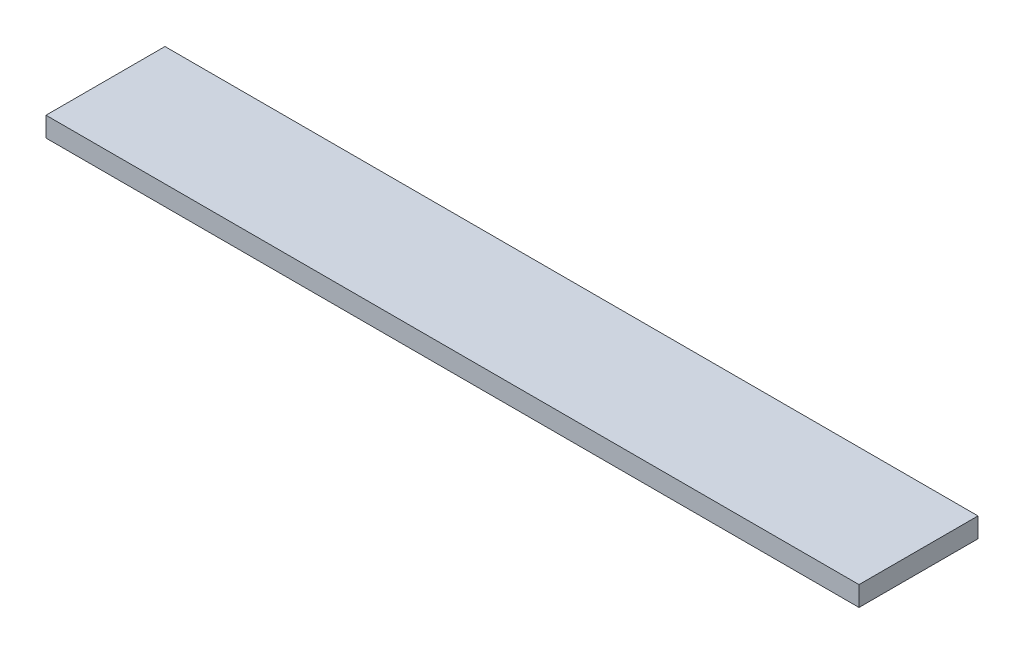
SolidWorks part; units mm, degrees
ref_plane "Front Plane" through (0, 0, 0) normal (0, 0, 1) x (1, 0, 0)
ref_plane "Top Plane" through (0, 0, 0) normal (0, 1, 0) x (1, 0, 0)
ref_plane "Right Plane" through (0, 0, 0) normal (1, 0, 0) x (0, 0, -1)
sketch "Sketch1" plane through (0, 0, 0) normal (0, 0, 1) x (1, 0, 0)
  line L1 (-28.3111, 16.1056) -> (12.6889, 16.1056)
  line L2 (-28.3111, 16.1056) -> (-28.3111, 10.1056)
  line L3 (-28.3111, 10.1056) -> (12.6889, 10.1056)
  line L4 (12.6889, 16.1056) -> (12.6889, 10.1056)
  line L5 (-7.8111, 10.1056) -> (-7.8111, 16.1056) construction
  line L6 (-28.3111, 13.1056) -> (12.6889, 13.1056) construction
  point P104 (-7.8111, 13.1056)
  dimension "D1" = 6
  dimension "D2" = 41
extrude "Boss-Extrude1" add sketch "Sketch1" along normal blind 1
move or copy body "Body-Move/Copy1" bodies to move or copy 102 copy no rotation origin (0, 13.1056, 0.25) rotation axis (1, 0, 0) rotation angle 90
